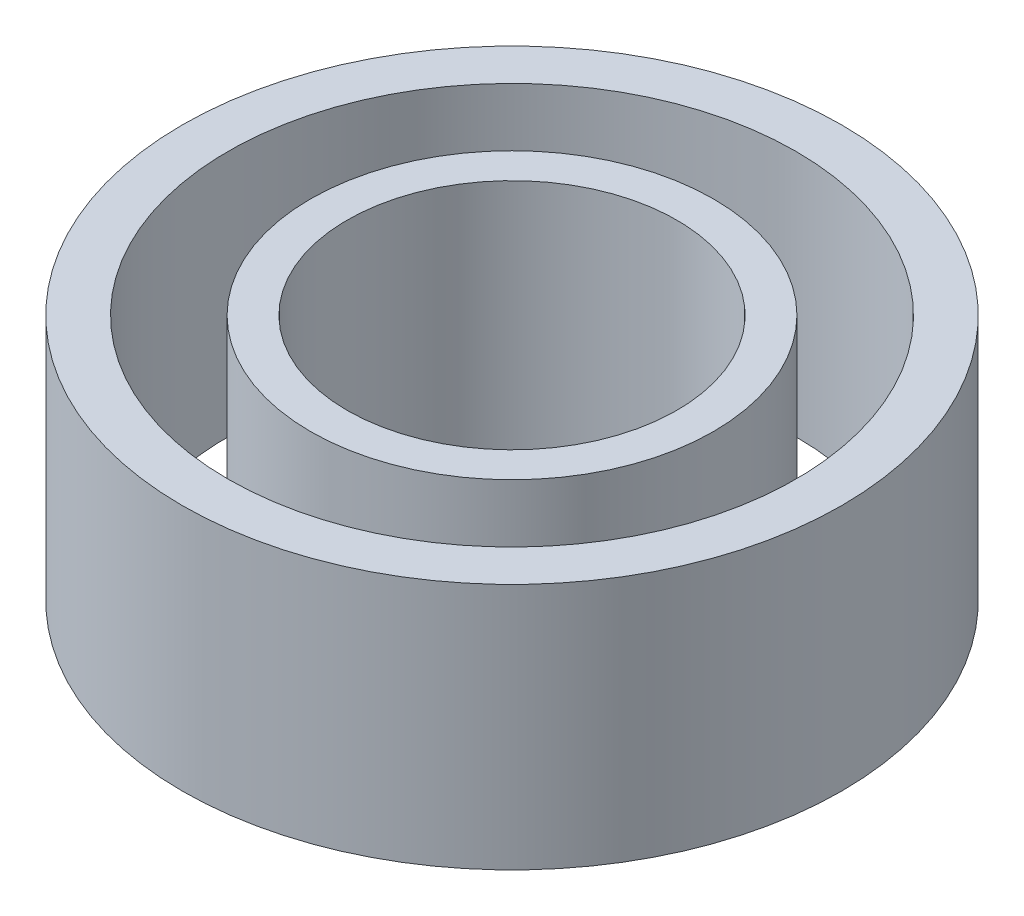
SolidWorks part; units mm, degrees
ref_plane "Front" through (0, 0, 0) normal (0, 0, 1) x (1, 0, 0)
ref_plane "Top" through (0, 0, 0) normal (0, 1, 0) x (1, 0, 0)
ref_plane "Right" through (0, 0, 0) normal (1, 0, 0) x (0, 0, -1)
sketch "Sketch1" plane through (0, 0, 0) normal (0, 1, 0) x (1, 0, 0)
  circle A0 centre (0, 0) radius 4
  dimension "D1" = 8
extrude "Boss-Extrude2" add sketch "Sketch1" along normal blind 3 contours A0
sketch "Sketch3" plane through (0, 3, 0) normal (0, 1, 0) x (1, 0, 0)
  circle A0 centre (0, 0) radius 2
  dimension "D1" = 4
extrude "Cut-Extrude2" cut sketch "Sketch3" against normal blind 3
sketch "Sketch4" plane through (0, 3, 0) normal (0, 1, 0) x (1, 0, 0)
  circle A0 centre (0, 0) radius 3.4444
  circle A1 centre (0, 0) radius 2.4444
  dimension "D1" = 1
extrude "Cut-Extrude3" cut sketch "Sketch4" against normal blind 3
